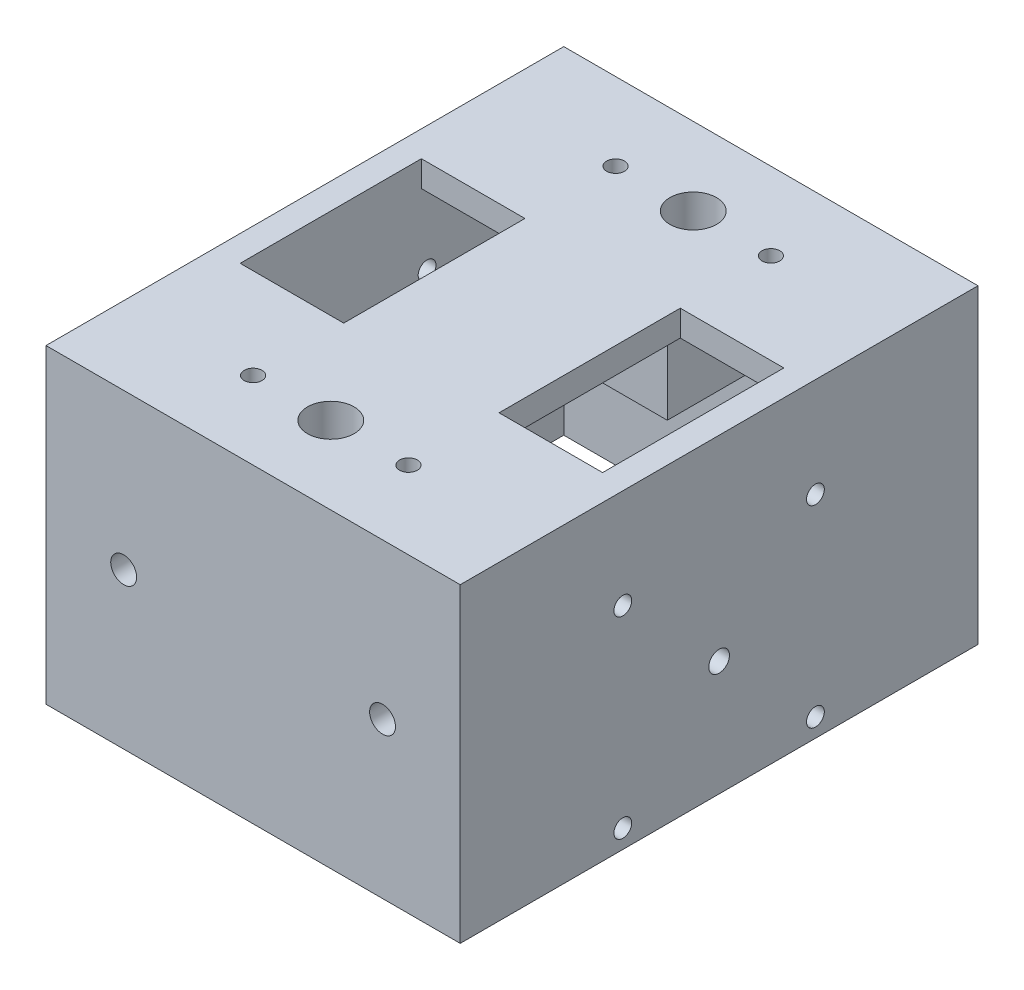
SolidWorks part; units mm, degrees
ref_plane "Front Plane" through (0, 0, 0) normal (0, 0, 1) x (1, 0, 0)
ref_plane "Top Plane" through (0, 0, 0) normal (0, 1, 0) x (1, 0, 0)
ref_plane "Right Plane" through (0, 0, 0) normal (1, 0, 0) x (0, 0, -1)
sketch "Sketch2" plane through (0, 0, 0) normal (0, 1, 0) x (1, 0, 0)
  line L1 (50.8, 63.5) -> (-50.8, 63.5)
  line L2 (50.8, 63.5) -> (50.8, -63.5)
  line L3 (50.8, -63.5) -> (-50.8, -63.5)
  line L4 (-50.8, 63.5) -> (-50.8, -63.5)
  line L5 (50.8, 63.5) -> (-50.8, -63.5) construction
  line L6 (50.8, -63.5) -> (-50.8, 63.5) construction
  point P0 (0, 0)
  dimension "D1" = 127
  dimension "D2" = 101.6
extrude "Boss-Extrude1" add sketch "Sketch2" along normal blind 76.2
shell "Shell1" thickness 6.35
sketch "Sketch4" plane through (0, 76.2, 0) normal (0, 1, 0) x (1, 0, 0)
  circle A0 centre (0, 44.45) radius 5.715
  circle A1 centre (0, -44.45) radius 5.715
  point P0 (-19.05, 44.45)
  point P1 (19.05, 44.45)
  point P3 (-19.05, -44.45)
  point P5 (19.05, -44.45)
  point P7 (0, 44.45)
  point P9 (0, -44.45)
  dimension "D1" = 11.43
  dimension "D2" = 11.43
hole_wizard "11/64 (0.17188) Diameter Hole1" positions "3DSketch1" profile "Sketch5" hole size "11/64" standard "ANSI Inch"
sketch3d "3DSketch1"
  point P0 (-19.05, 76.2, -44.45)
  point P3 (19.05, 76.2, -44.45)
  point P6 (-19.05, 76.2, 44.45)
  point P9 (19.05, 76.2, 44.45)
sketch "Sketch5" plane through (-19.05, 76.2, -44.45) normal (1, 0, 0) x (0, 0, 1)
  line L0 (0, 0) -> (0, 26.7116)
  line L1 (0, 26.7116) -> (2.1829, 25.4)
  line L2 (2.1829, 25.4) -> (2.1829, 0)
  line L5 (2.1829, 0) -> (0, 0)
  line L10 (0, 26.7116) -> (-2.1829, 25.4) construction
  line L11 (0, -6.35) -> (0, 107.95) construction
  dimension "Hole Dia." = 4.3658
  dimension "Hole Depth" = 25.4
  dimension "Drill Angle" = 118
extrude "Cut-Extrude2" cut sketch "Sketch4" against normal through all
sketch "Sketch6" plane through (0, 69.85, 0) normal (0, -1, 0) x (1, 0, 0)
  line L0 (-44.45, 57.15) -> (44.45, 57.15) construction
  line L1 (9.525, 28.575) -> (-9.525, 28.575)
  line L2 (9.525, 28.575) -> (9.525, 57.15)
  line L3 (9.525, 57.15) -> (-9.525, 57.15)
  line L4 (-9.525, 28.575) -> (-9.525, 57.15)
  line L5 (9.525, 28.575) -> (-9.525, 57.15) construction
  line L6 (9.525, 57.15) -> (-9.525, 28.575) construction
  line L7 (-44.45, 0) -> (44.45, 0)
  line L8 (-44.45, -57.15) -> (-44.45, 57.15) construction
  line L9 (44.45, 57.15) -> (44.45, -57.15) construction
  line L10 (9.525, -57.15) -> (-9.525, -28.575) construction
  line L11 (9.525, -28.575) -> (-9.525, -57.15) construction
  line L12 (-9.525, -28.575) -> (-9.525, -57.15)
  line L13 (9.525, -57.15) -> (-9.525, -57.15)
  line L14 (9.525, -28.575) -> (9.525, -57.15)
  line L15 (9.525, -28.575) -> (-9.525, -28.575)
  line L16 (44.45, 57.15) -> (44.45, -57.15) construction
  point P0 (0, 42.8625)
  point P18 (0, -42.8625)
  circle M1 centre (0, 44.45) radius 5.715
  circle M2 centre (0, -44.45) radius 5.715
  line M8 (-44.45, -57.15) -> (44.45, -57.15)
  line M10 (44.45, 57.15) -> (-44.45, 57.15)
  dimension "D1" = 19.05
  dimension "D2" = 28.575
  dimension "D3" = 34.925
extrude "Boss-Extrude2" add sketch "Sketch6" along normal blind 25.4 contours L4 L1 L2 M10 M1 | L14 L15 L12 M8 M2
sketch "Sketch7" plane through (-50.8, 0, 0) normal (-1, 0, 0) x (0, 0, 1)
  line L0 (-63.5, 0) -> (63.5, 0) construction
  line L3 (-63.5, 76.2) -> (-63.5, 0) construction
  line L4 (63.5, 76.2) -> (63.5, 0) construction
  point P0 (-23.622, 51.816)
  point P1 (23.622, 51.816)
  point P3 (23.622, 4.572)
  point P5 (-23.622, 4.572)
  point P7 (0, 28.194)
  dimension "D1" = 4.572
  dimension "D2" = 39.878
  dimension "D3" = 39.878
  dimension "D4" = 51.816
  dimension "D5" = 39.878
  dimension "D6" = 4.572
  dimension "D7" = 39.878
  dimension "D8" = 51.816
hole_wizard "11/64 (0.17188) Diameter Hole2" positions "3DSketch2" profile "Sketch8" hole size "11/64" standard "ANSI Inch"
sketch3d "3DSketch2"
  point P0 (-50.8, 51.816, -23.622)
  point P3 (-50.8, 4.572, -23.622)
  point P6 (-50.8, 51.816, 23.622)
  point P9 (-50.8, 4.572, 23.622)
sketch "Sketch8" plane through (-50.8, 51.816, -23.622) normal (0, 1, 0) x (0, 0, 1)
  line L0 (0, 0) -> (0, 128.3116)
  line L1 (0, 128.3116) -> (2.1829, 127)
  line L2 (2.1829, 127) -> (2.1829, 0)
  line L5 (2.1829, 0) -> (0, 0)
  line L10 (0, 128.3116) -> (-2.1829, 127) construction
  line L11 (0, -6.35) -> (0, 107.95) construction
  dimension "Hole Dia." = 4.3658
  dimension "Hole Depth" = 127
  dimension "Drill Angle" = 118
sketch "Sketch9" plane through (-50.8, 0, 0) normal (-1, 0, 0) x (0, 0, 1)
  circle A0 centre (0, 28.194) radius 3.81
  dimension "D1" = 7.62
extrude "Cut-Extrude3" cut sketch "Sketch9" against normal up to next
sketch "Sketch10" plane through (0, 69.85, 0) normal (0, -1, 0) x (-1, 0, 0)
  line L0 (44.45, 57.15) -> (44.45, -57.15) construction
  line L1 (19.05, 22.225) -> (44.45, 22.225)
  line L2 (19.05, 22.225) -> (19.05, -22.225)
  line L3 (19.05, -22.225) -> (44.45, -22.225)
  line L4 (44.45, 22.225) -> (44.45, -22.225)
  line L5 (44.45, -57.15) -> (-44.45, -57.15) construction
  line L6 (0, 57.15) -> (0, -57.15)
  line L7 (-44.45, 57.15) -> (44.45, 57.15) construction
  line L8 (-44.45, 22.225) -> (-44.45, -22.225)
  line L9 (-19.05, -22.225) -> (-44.45, -22.225)
  line L10 (-19.05, 22.225) -> (-19.05, -22.225)
  line L11 (-19.05, 22.225) -> (-44.45, 22.225)
  line M3 (-44.45, 57.15) -> (-44.45, -57.15)
  line M9 (44.45, -57.15) -> (44.45, 57.15)
  dimension "D1" = 25.4
  dimension "D2" = 44.45
  dimension "D3" = 0
  dimension "D4" = 34.925
extrude "Cut-Extrude5" cut sketch "Sketch10" against normal through all contours L2 L3 L1 M9 | L10 L11 L9 M3
sketch "Sketch11" plane through (0, 0, 63.5) normal (0, 0, 1) x (1, 0, 0)
  line L0 (-50.8, 76.2) -> (-50.8, 0) construction
  line L1 (-50.8, 0) -> (50.8, 0) construction
  line L2 (0, 0) -> (0, 76.2)
  circle A0 centre (-31.75, 38.1) radius 3.175
  circle A1 centre (31.75, 38.1) radius 3.175
  dimension "D1" = 6.35
  dimension "D2" = 19.05
  dimension "D3" = 38.1
extrude "Cut-Extrude6" cut sketch "Sketch11" against normal through all contours A0 | A1
sketch "Sketch13" plane through (50.8, 0, 0) normal (1, 0, 0) x (0, 0, -1)
  circle A0 centre (0, 28.194) radius 2.54
  dimension "D1" = 5.08
extrude "Cut-Extrude7" cut sketch "Sketch13" against normal up to next
sketch "Sketch14" plane through (-50.8, 0, 0) normal (-1, 0, 0) x (0, 0, 1)
  line L1 (20.6375, 7.5565) -> (-20.6375, 7.5565)
  line L2 (20.6375, 7.5565) -> (20.6375, 48.8315)
  line L3 (20.6375, 48.8315) -> (-20.6375, 48.8315)
  line L4 (-20.6375, 7.5565) -> (-20.6375, 48.8315)
  line L5 (20.6375, 7.5565) -> (-20.6375, 48.8315) construction
  line L6 (20.6375, 48.8315) -> (-20.6375, 7.5565) construction
  point P0 (0, 28.194)
  dimension "D1" = 41.275
extrude "Cut-Extrude8" cut sketch "Sketch14" against normal blind 2.032
